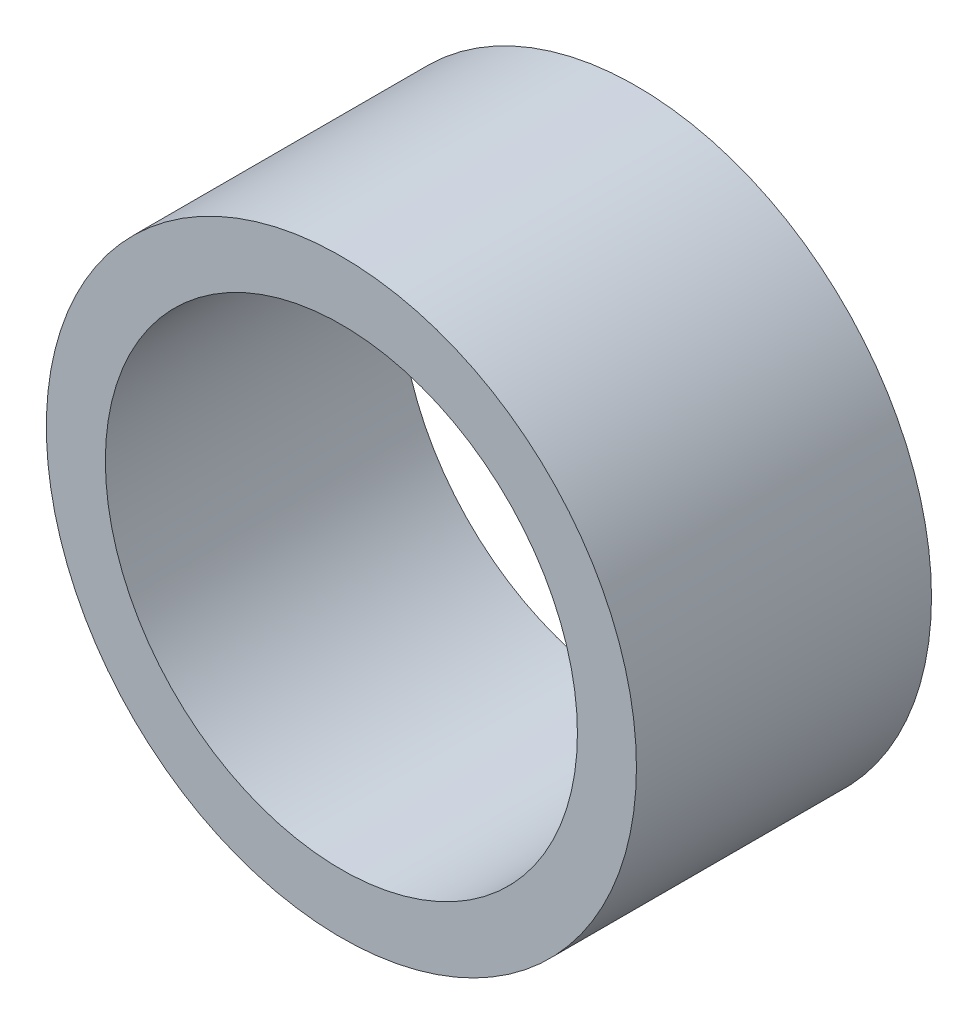
SolidWorks part; units mm, degrees
material "POLYURETHANE (11671)"
ref_plane "Front Plane" through (0, 0, 0) normal (0, 0, 1) x (1, 0, 0)
ref_plane "Top Plane" through (0, 0, 0) normal (0, 1, 0) x (1, 0, 0)
ref_plane "Right Plane" through (0, 0, 0) normal (1, 0, 0) x (0, 0, -1)
sketch "Sketch1" plane through (0, 0, 0) normal (0, 0, 1) x (1, 0, 0)
  circle A0 centre (0, 0) radius 10.16
  circle A1 centre (0, 0) radius 12.7
  dimension "D1" = 20.32
  dimension "D2" = 25.4
extrude "Boss-Extrude1" add sketch "Sketch1" along normal blind 12.7
